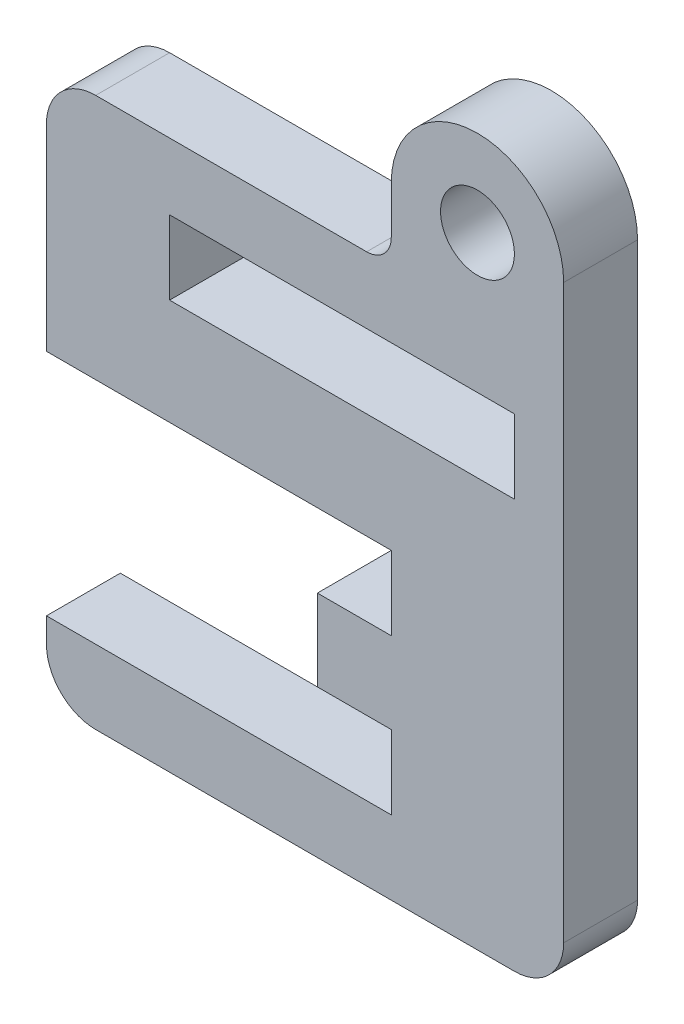
SolidWorks part; units mm, degrees
ref_plane "Front Plane" through (0, 0, 0) normal (0, 0, 1) x (1, 0, 0)
ref_plane "Top Plane" through (0, 0, 0) normal (0, 1, 0) x (1, 0, 0)
ref_plane "Right Plane" through (0, 0, 0) normal (1, 0, 0) x (0, 0, -1)
sketch "Sketch2" plane through (0, 0, 0) normal (0, 0, 1) x (1, 0, 0)
  line L1 (-1.6038, 21.0862) -> (-1.6038, -2.1338)
  line L2 (-3.6038, -4.1338) -> (-20.6038, -4.1338)
  line L3 (-22.6038, -2.1338) -> (-22.6038, 16.1662)
  line L4 (-20.6038, 18.1662) -> (-9.6038, 18.1662)
  line L5 (-8.6038, 19.1662) -> (-8.6038, 21.0862)
  arc A1 (-1.6038, -2.1338) -> (-3.6038, -4.1338) centre (-3.6038, -2.1338) cw
  arc A2 (-20.6038, -4.1338) -> (-22.6038, -2.1338) centre (-20.6038, -2.1338) cw
  arc A3 (-22.6038, 16.1662) -> (-20.6038, 18.1662) centre (-20.6038, 16.1662) cw
  arc A4 (-9.6038, 18.1662) -> (-8.6038, 19.1662) centre (-9.6038, 19.1662) ccw
  arc A5 (-8.6038, 21.0862) -> (-1.6038, 21.0862) centre (-5.1038, 21.0862) cw
  dimension "D2" = 2
  dimension "D3" = 1
  dimension "D4" = 2
  dimension "D5" = 2
  dimension "D1" = 22.3
  dimension "D6" = 21
  dimension "D7" = 2.92
extrude "Boss-Extrude1" add sketch "Sketch2" along normal blind 3
sketch "Sketch4" plane through (0, 0, 3) normal (0, 0, 1) x (1, 0, 0)
  line L0 (-22.6038, 16.1662) -> (-22.6038, -2.1338) construction
  line L1 (-17.6038, 15.4662) -> (-3.6038, 15.4662)
  line L2 (-17.6038, 15.4662) -> (-17.6038, 12.4662)
  line L3 (-17.6038, 12.4662) -> (-3.6038, 12.4662)
  line L4 (-3.6038, 15.4662) -> (-3.6038, 12.4662)
  line L5 (-22.6038, 8.1662) -> (-8.6038, 8.1662)
  line L6 (-22.6038, 8.1662) -> (-22.6038, 5.1662)
  line L7 (-22.6038, 5.1662) -> (-8.6038, 5.1662)
  line L8 (-8.6038, 8.1662) -> (-8.6038, 5.1662)
  line L9 (-1.6038, -2.1338) -> (-1.6038, 21.0862) construction
  line L10 (-9.6038, 18.1662) -> (-20.6038, 18.1662) construction
  line L11 (-22.6038, 1.8662) -> (-8.6038, 1.8662)
  line L12 (-22.6038, 1.8662) -> (-22.6038, -1.1338)
  line L13 (-22.6038, -1.1338) -> (-8.6038, -1.1338)
  line L14 (-8.6038, 1.8662) -> (-8.6038, -1.1338)
  dimension "D1" = 14
  dimension "D2" = 3
  dimension "D3" = 3
  dimension "D4" = 4.3
  dimension "D5" = 14
  dimension "D6" = 2
  dimension "D7" = 2.7
  dimension "D8" = 3
  dimension "D9" = 3.3
extrude "Cut-Extrude1" cut sketch "Sketch4" against normal blind 3
sketch "Sketch5" plane through (0, 0, 3) normal (0, 0, 1) x (1, 0, 0)
  circle A0 centre (-5.1038, 21.0862) radius 1.5
  arc A2 (-1.6038, 21.0862) -> (-8.6038, 21.0862) centre (-5.1038, 21.0862) ccw construction
  dimension "D1" = 3
extrude "Cut-Extrude2" cut sketch "Sketch5" against normal blind 3
sketch "Sketch6" plane through (0, 0, 3) normal (0, 0, 1) x (1, 0, 0)
  line L0 (-8.6038, 1.8662) -> (-22.6038, 1.8662) construction
  line L1 (-22.6038, 5.1662) -> (-11.6038, 5.1662)
  line L2 (-22.6038, 5.1662) -> (-22.6038, 1.8662)
  line L3 (-22.6038, 1.8662) -> (-11.6038, 1.8662)
  line L4 (-11.6038, 5.1662) -> (-11.6038, 1.8662)
  dimension "D1" = 11
extrude "Cut-Extrude3" cut sketch "Sketch6" against normal blind 3
